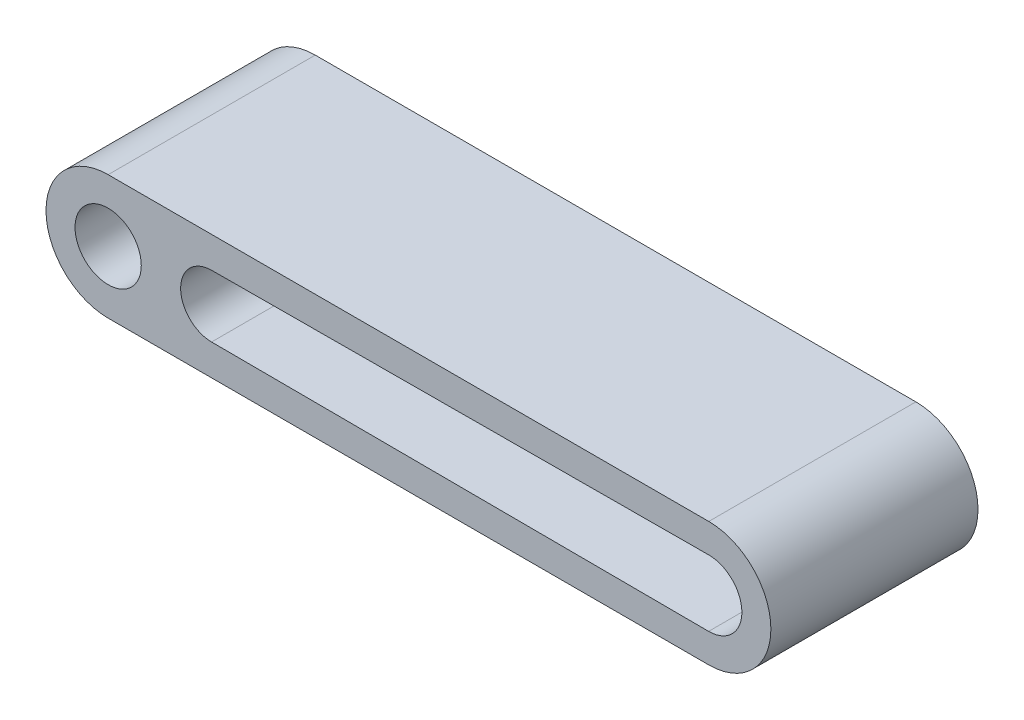
SolidWorks part; units mm, degrees
ref_plane "Alzado" through (0, 0, 0) normal (0, 0, 1) x (1, 0, 0)
ref_plane "Planta" through (0, 0, 0) normal (0, 1, 0) x (1, 0, 0)
ref_plane "Vista lateral" through (0, 0, 0) normal (1, 0, 0) x (0, 0, -1)
sketch "Croquis1" plane through (0, 0, 0) normal (0, 0, 1) x (1, 0, 0)
  line L0 (0, 0) -> (29.0002, 0) construction
  line L1 (0, 3) -> (29.0002, 3)
  line L2 (0, -3) -> (29.0002, -3)
  line L3 (5, 0) -> (60, 0) construction
  line L4 (4.9938, 1.5) -> (28.9935, 1.6)
  line L5 (4.9938, -1.5) -> (28.9935, -1.6)
  arc A0 (0, 3) -> (0, -3) centre (0, 0) ccw
  arc A1 (29.0002, -3) -> (29.0002, 3) centre (29.0002, 0) ccw
  circle A2 centre (0, 0) radius 1.6
  arc A3 (28.9935, -1.6) -> (28.9935, 1.6) centre (29.0002, 0) ccw
  arc A4 (4.9938, 1.5) -> (4.9938, -1.5) centre (5, 0) ccw
  point P3 (14.5001, 0)
  point P14 (35, 0)
  dimension "D1" = 3
  dimension "D3" = 3.2
  dimension "D4" = 24
  dimension "D5" = 1.5
  dimension "D2" = 5
extrude "Saliente-Extruir1" add sketch "Croquis1" along normal blind 10
